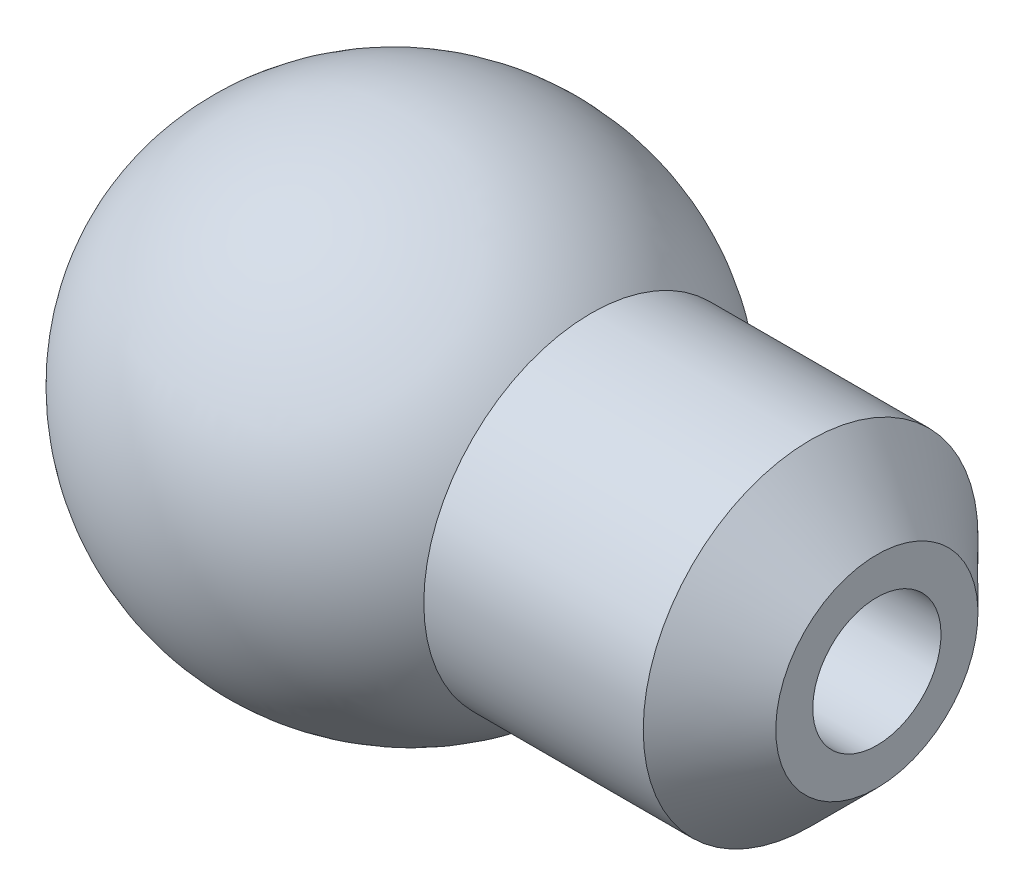
SolidWorks part; units mm, degrees
ref_plane "Front Plane" through (0, 0, 0) normal (0, 0, 1) x (1, 0, 0)
ref_plane "Top Plane" through (0, 0, 0) normal (0, 1, 0) x (1, 0, 0)
ref_plane "Right Plane" through (0, 0, 0) normal (1, 0, 0) x (0, 0, -1)
sketch "Sketch1" plane through (0, 0, 0) normal (0, 0, 1) x (1, 0, 0)
  line L2 (0, 26) -> (60, 26)
  line L4 (60, 26) -> (60, 41)
  line L6 (60, 41) -> (33.1299, 67.8701)
  line L7 (33.1299, 67.8701) -> (-55.8487, 67.8701)
  line L10 (-55.8487, 67.8701) -> (-55.8487, 90.7034) construction
  line L11 (-55.8487, 90.7034) -> (-55.8487, -92.381) construction
  line L13 (0, 0) -> (9.4604, 0) construction
  line L14 (0, 26) -> (0, 0)
  line L16 (9.4604, 0) -> (-277.6884, 0) construction
  line L18 (-315.9646, 100) -> (97.4701, 100) construction
  line L19 (-315.9646, -100) -> (108.0637, -100) construction
  line L20 (-240, 0) -> (0, 0)
  arc A0 (-240, 0) -> (-55.8487, 67.8701) centre (-132.4481, -8.0566) cw
  dimension "D12" = 100
  dimension "D10" = 240
  dimension "D2" = 26
  dimension "D3" = 60
  dimension "D4" = 15
  dimension "D6" = 135
  dimension "D7" = 38
  dimension "D13" = 100
revolve "Revolve2" add sketch "Sketch1" angle 360 about L20
